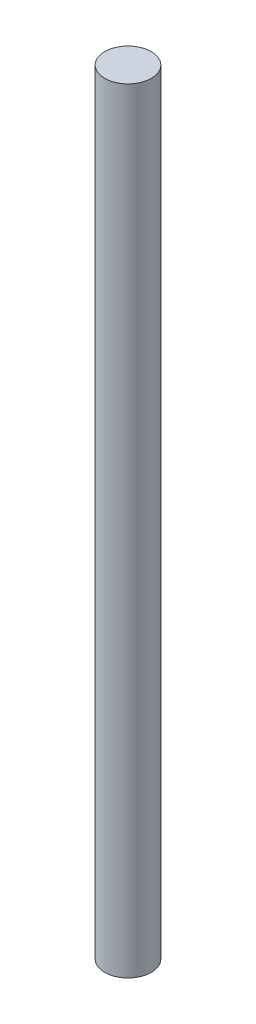
SolidWorks part; units mm, degrees
ref_plane "前视基准面" through (0, 0, 0) normal (0, 0, 1) x (1, 0, 0)
ref_plane "上视基准面" through (0, 0, 0) normal (0, 1, 0) x (1, 0, 0)
ref_plane "右视基准面" through (0, 0, 0) normal (1, 0, 0) x (0, 0, -1)
other "Configuration Table"
sketch "Sketch1" plane through (0, 0, 0) normal (0, 1, 0) x (1, 0, 0)
  circle A0 centre (0, 0) radius 6
extrude "Boss-Extrude1" add sketch "Sketch1" along normal blind 200
